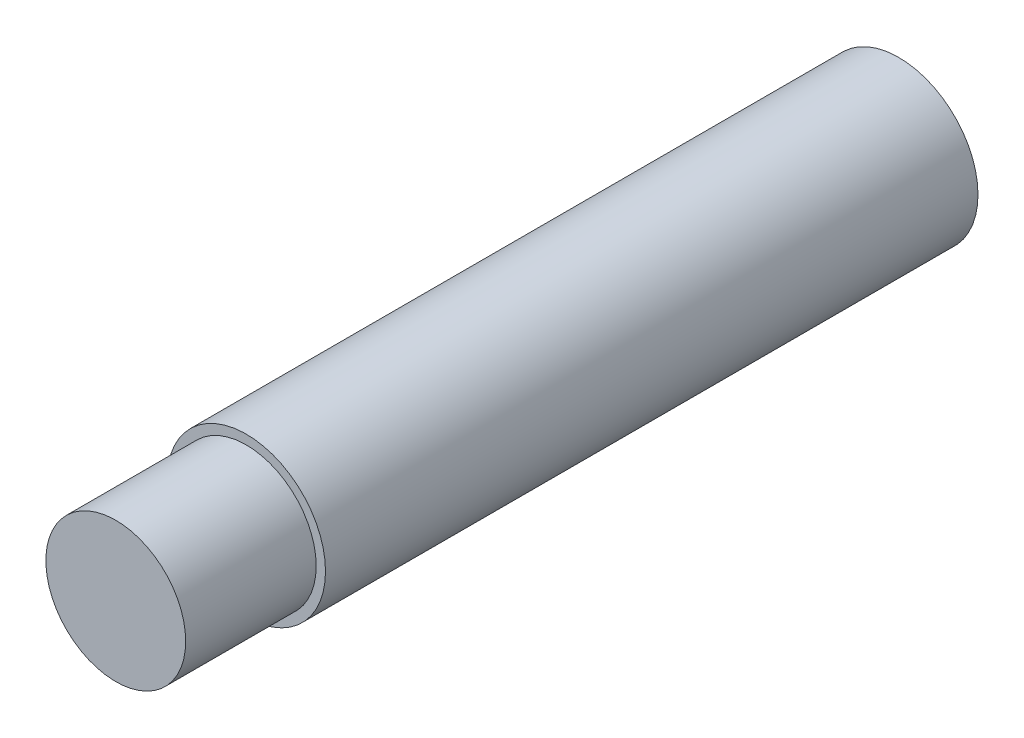
SolidWorks part; units mm, degrees
ref_plane "Front Plane" through (0, 0, 0) normal (0, 0, 1) x (1, 0, 0)
ref_plane "Top Plane" through (0, 0, 0) normal (0, 1, 0) x (1, 0, 0)
ref_plane "Right Plane" through (0, 0, 0) normal (1, 0, 0) x (0, 0, -1)
sketch "Sketch2" plane through (0, 0, 0) normal (0, 0, 1) x (1, 0, 0)
  circle A0 centre (0, 0) radius 4.25
  dimension "D1" = 8.5
extrude "Boss-Extrude1" add sketch "Sketch2" along normal blind 35
sketch "Sketch3" plane through (0, 0, 35) normal (0, 0, 1) x (1, 0, 0)
  circle A0 centre (0, 0) radius 3.75
  dimension "D1" = 7.5
extrude "Boss-Extrude2" add sketch "Sketch3" along normal blind 7 and the other way blind 29.5
